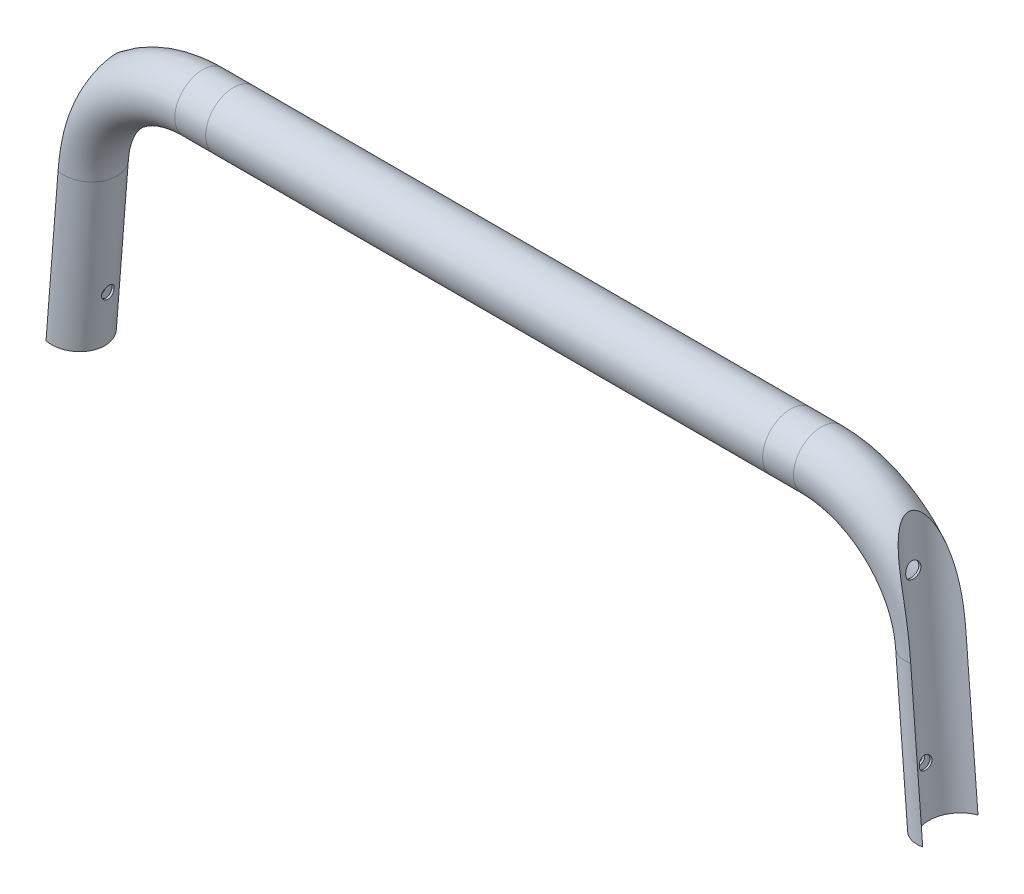
SolidWorks part; units mm, degrees
ref_plane "Front Plane" through (0, 0, 0) normal (0, 0, 1) x (1, 0, 0)
ref_plane "Top Plane" through (0, 0, 0) normal (0, 1, 0) x (1, 0, 0)
ref_plane "Right Plane" through (0, 0, 0) normal (1, 0, 0) x (0, 0, -1)
sketch "Sketch1" plane through (0, 0, 0) normal (0, 0, 1) x (1, 0, 0)
  line L0 (-110, 0) -> (110, 0)
  line L1 (0, 0) -> (0, -80) construction
  line L3 (-171.8, -101.9) -> (-167.044, -41.4693)
  line L4 (-122.1827, 0) -> (-110, 0)
  line L5 (171.8, -101.9) -> (167.044, -41.4693)
  line L6 (122.1827, 0) -> (110, 0)
  arc A0 (167.044, -41.4693) -> (122.1827, 0) centre (122.1827, -45) ccw
  arc A1 (-122.1827, 0) -> (-167.044, -41.4693) centre (-122.1827, -45) ccw
  point P4 (0, 0)
  point P11 (0, -80)
  dimension "D5" = 45
  dimension "D1" = 220
  dimension "D2" = 101.9
  dimension "D3" = 94.5
  dimension "D4" = 94.5
  dimension "D6" = 101.9
  dimension "D7" = 343.6
ref_plane "Plane1" through (-171.8, -101.9, 0) normal (-0.0785, -0.9969, 0) x (-0.9969, 0.0785, 0)
sketch "Sketch2" plane through (-171.8, -101.9, 0) normal (-0.0785, -0.9969, 0) x (-0.9969, 0.0785, 0)
  line L0 (-41.4693, 0) -> (0, 0) construction
  circle A0 centre (0, 0) radius 11
  circle A1 centre (0, 0) radius 10.2
  dimension "D1" = 0.8
sweep "Sweep1" add profiles "Sketch2" path "Sketch1"
sketch "Sketch3" plane through (9.0279, -114.7104, 0) normal (0.0785, -0.9969, 0) x (0.9969, 0.0785, 0)
  line L0 (163.2754, 0) -> (167.2754, 0) construction
  circle A0 centre (167.2754, 0) radius 11.2358
  dimension "D2" = 22.4716
  dimension "D1" = 4
extrude "Cut-Extrude1" cut sketch "Sketch3" against normal through all
mirror "Mirror1" about plane through (0, 0, 0) normal (1, 0, 0) of "Cut-Extrude1"
sketch "Sketch6" plane through (9.0279, -114.7104, 0) normal (0.0785, -0.9969, 0) x (0.9969, 0.0785, 0)
  line L0 (163.2754, 0) -> (167.2754, 0) construction
  arc A0 (163.2185, 10.4778) -> (163.2185, -10.4778) centre (167.2754, 0) ccw
  arc A2 (160.8913, 10.2032) -> (160.8913, -10.2032) centre (167.2754, 0) ccw
  arc A3 (160.8913, -10.2032) -> (163.2185, -10.4778) centre (163.2754, 0) ccw
  circle A4 centre (167.2754, 0) radius 12.0358 construction
  circle A5 centre (167.2754, 0) radius 11.2358 construction
  arc A6 (163.2185, 10.4778) -> (160.8913, 10.2032) centre (163.2754, 0) ccw
  dimension "D1" = 0.8
extrude "Boss-Extrude1" add sketch "Sketch6" against normal up to next
mirror "Mirror2" about plane through (0, 0, 0) normal (1, 0, 0) of "Boss-Extrude1"
sketch "Sketch7" plane through (9.0279, -114.7104, 0) normal (0.0785, -0.9969, 0) x (0.9969, 0.0785, 0)
  line L0 (152.2754, 0) -> (163.2754, 0)
  arc A0 (164.62, 10.9175) -> (164.62, -10.9175) centre (163.2754, 0) ccw construction
ref_plane "Plane2" through (171.8, -101.9, 0) normal (0.9969, 0.0785, 0) x (0, 0, -1)
sketch "Sketch8" plane through (171.8, -101.9, 0) normal (0.9969, 0.0785, 0) x (0, 0, -1)
  line L0 (0, 0.0022) -> (0, 19.1022) construction
  circle A0 centre (0, 19.1022) radius 2.5
  dimension "D1" = 19.1
extrude "Cut-Extrude2" cut sketch "Sketch8" against normal up to surface (332.252 mm away)
mirror "Mirror3" about plane through (0, 0, 0) normal (1, 0, 0) of "Cut-Extrude2"
ref_plane "Plane3" through (180, 0, 0) normal (1, 0, 0) x (0, 0, -1)
sketch "Sketch9" plane through (180, 0, 0) normal (1, 0, 0) x (0, 0, -1)
  circle A0 centre (0, -20) radius 3
  dimension "D1" = 20
extrude "Cut-Extrude3" cut sketch "Sketch9" against normal up to next
